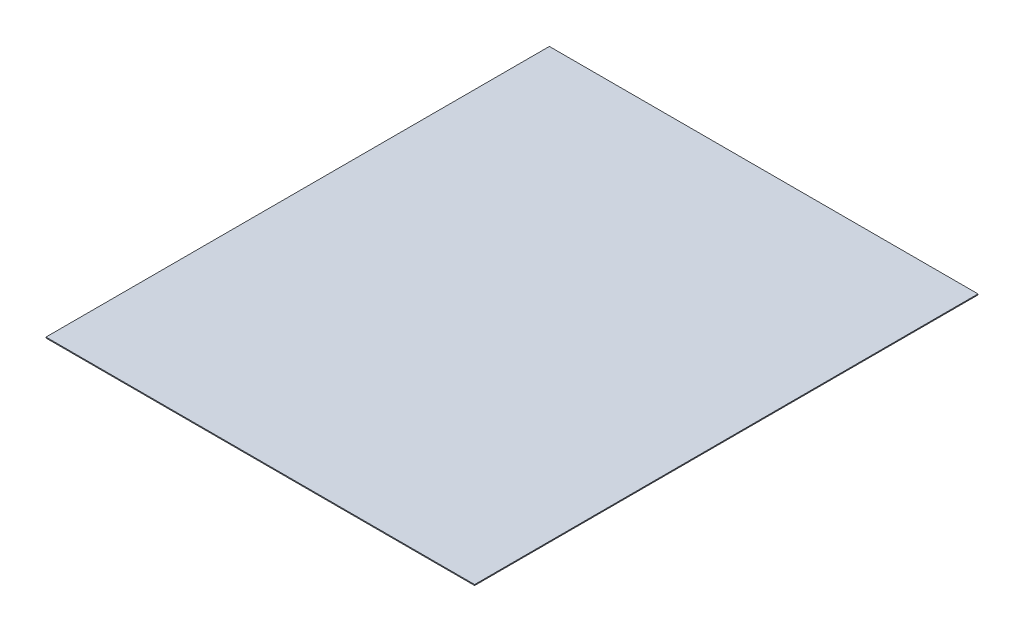
SolidWorks part; units mm, degrees
ref_plane "Front Plane" through (0, 0, 0) normal (0, 0, 1) x (1, 0, 0)
ref_plane "Top Plane" through (0, 0, 0) normal (0, 1, 0) x (1, 0, 0)
ref_plane "Right Plane" through (0, 0, 0) normal (1, 0, 0) x (0, 0, -1)
other "Configuration Table"
sketch "Sketch1" plane through (0, 0, 0) normal (0, 0, 1) x (1, 0, 0)
  line L1 (1.5, 120) -> (698.5, 120)
  line L2 (1.5, 120) -> (1.5, 121.5)
  line L3 (1.5, 121.5) -> (698.5, 121.5)
  line L4 (698.5, 120) -> (698.5, 121.5)
extrude "OVEN_dis_alt_1" add sketch "Sketch1" against normal blind 818.5 separate body
